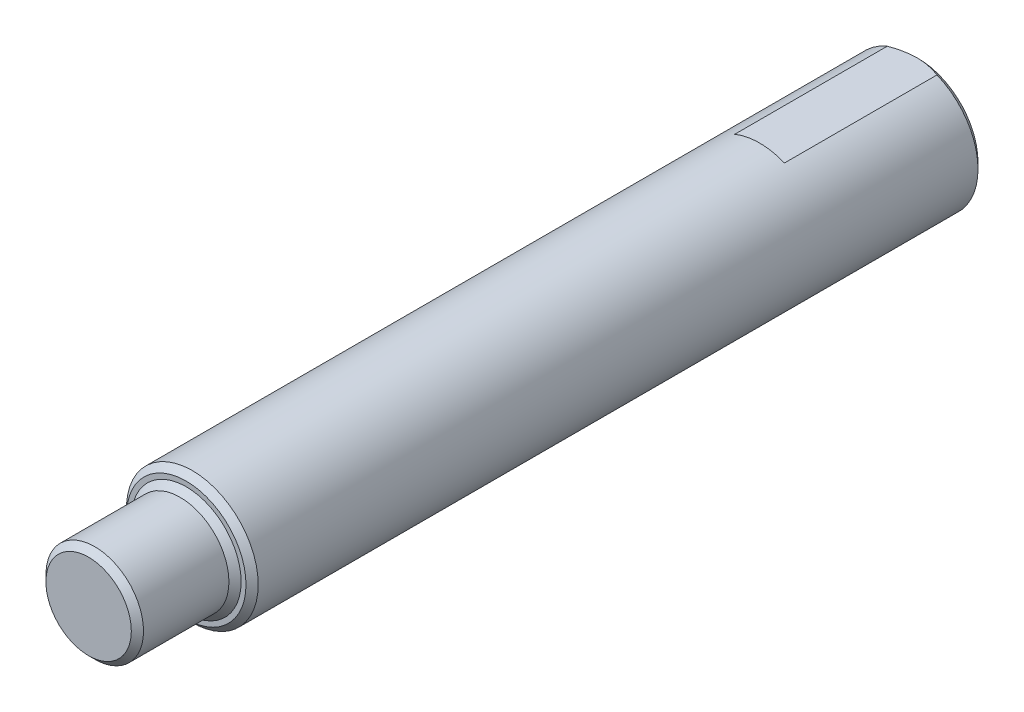
SolidWorks part; units mm, degrees
material "AISI 1045 Steel, cold drawn"
ref_plane "前视基准面" through (0, 0, 0) normal (0, 0, 1) x (1, 0, 0)
ref_plane "上视基准面" through (0, 0, 0) normal (0, 1, 0) x (1, 0, 0)
ref_plane "右视基准面" through (0, 0, 0) normal (1, 0, 0) x (0, 0, -1)
sketch "草图1" plane through (0, 0, 0) normal (0, 0, 1) x (1, 0, 0)
  circle A0 centre (0, 0) radius 5.4
  dimension "D1" = 10.8
extrude "拉伸1" add sketch "草图1" along normal blind 60
chamfer "倒角1" distance 0.5 angle 45 2 edges at (5.4, 0, 0) (5.4, 0, 60)
sketch "草图2" plane through (0, 0, 60) normal (0, 0, 1) x (1, 0, 0)
  circle A0 centre (0, 0) radius 4
  dimension "D1" = 8
extrude "拉伸2" add sketch "草图2" along normal blind 8
cosmetic thread "装饰螺纹线1" parameters "D2"=7
chamfer "倒角2" distance 0.5 angle 45 1 edges at (4, 0, 68)
hole_wizard "M5 螺纹孔1" positions "草图4" profile "草图3" tap size "M5" standard "GB"
sketch "草图4" plane through (0, 0, 0) normal (0, 0, -1) x (-1, 0, 0)
  point P1 (0, 0)
sketch "草图3" plane through (0, 0, 0) normal (1, 0, 0) x (0, 1, 0)
  line L0 (0, 0) -> (0, 13.6618)
  line L1 (0, 13.6618) -> (2.1, 12.4)
  line L2 (2.1, 12.4) -> (2.1, 0)
  line L5 (2.1, 0) -> (0, 0)
  line L10 (0, 13.6618) -> (-2.1, 12.4) construction
  line L11 (0, -6.35) -> (0, 107.95) construction
  dimension "螺纹孔钻头直径" = 4.2
  dimension "螺纹孔钻头深度" = 12.4
  dimension "导头角度" = 118
cosmetic thread "孔螺蚊线1" parameters "D1"=10, "D2"=5
chamfer "倒角3" distance 0.5 angle 45 1 edges at (-2.1, 0, 0)
sketch "草图5" plane through (0, 0, 0) normal (0, 0, 1) x (1, 0, 0)
  line L0 (0, 0) -> (0, 5) construction
  line L1 (-5, 8) -> (5, 8)
  line L2 (-5, 8) -> (-5, 5)
  line L3 (-5, 5) -> (5, 5)
  line L4 (5, 8) -> (5, 5)
  dimension "D1" = 5
  dimension "D2" = 3
  dimension "D3" = 10
extrude "拉伸3" cut sketch "草图5" along normal blind 13
mirror "镜向1" about plane through (0, 0, 0) normal (0, 1, 0) of "拉伸3"
chamfer "倒角4" distance 0.5 angle 45 1 edges at (4, 0, 60)
